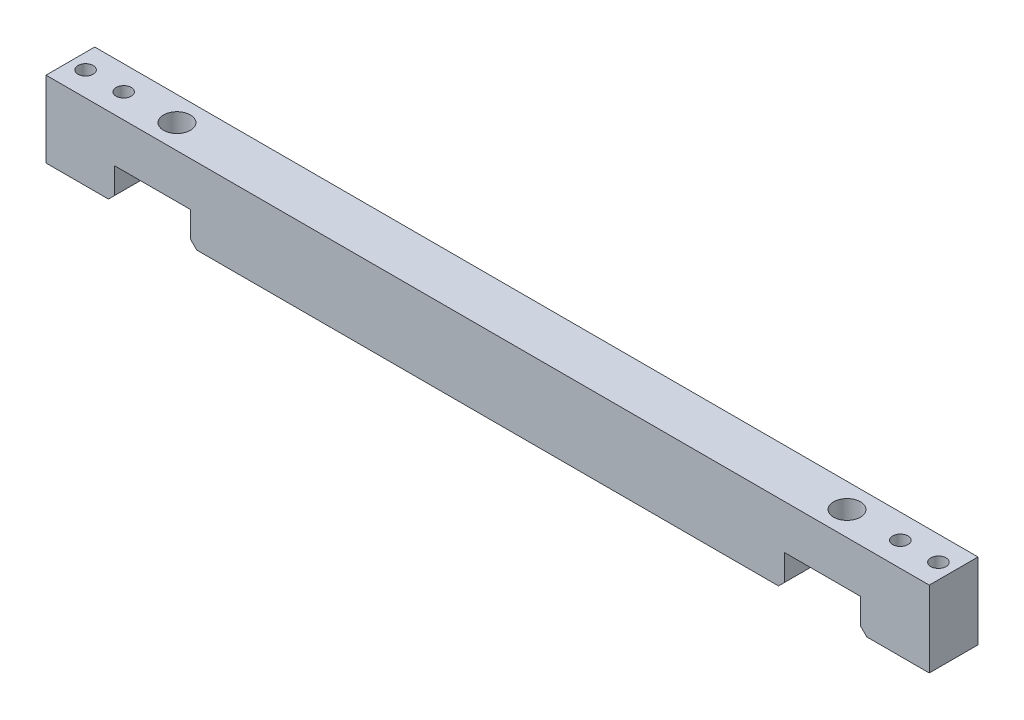
SolidWorks part; units mm, degrees
material "7075-T6 (SN)"
ref_plane "Front Plane" through (0, 0, 0) normal (0, 0, 1) x (1, 0, 0)
ref_plane "Top Plane" through (0, 0, 0) normal (0, 1, 0) x (1, 0, 0)
ref_plane "Right Plane" through (0, 0, 0) normal (1, 0, 0) x (0, 0, -1)
sketch "Sketch1" plane through (0, 0, 0) normal (0, 1, 0) x (1, 0, 0)
  line L1 (-145, 8) -> (145, 8)
  line L2 (-145, 8) -> (-145, -8)
  line L3 (-145, -8) -> (145, -8)
  line L4 (145, 8) -> (145, -8)
  line L5 (-145, 8) -> (145, -8) construction
  line L6 (-145, -8) -> (145, 8) construction
  point P0 (0, 0)
  dimension "D1" = 290
  dimension "D2" = 16
extrude "Boss-Extrude1" add sketch "Sketch1" along normal mid plane 25
hole_wizard "M5 Tapped Hole1" positions "Sketch4" profile "Sketch5" tap size "M5" standard "ISO" end condition through all
sketch "Sketch4" plane through (0, 12.5, 0) normal (0, 1, 0) x (1, 0, 0)
  point P0 (-110, 0)
  point P2 (110, 0)
  dimension "D1" = 110
  dimension "D2" = 110
sketch "Sketch5" plane through (-110, 12.5, 0) normal (1, 0, 0) x (0, 0, 1)
  line L0 (0, 0) -> (0, 25)
  line L1 (0, 25) -> (2.1, 25)
  line L2 (2.1, 25) -> (2.1, 0)
  line L5 (2.1, 0) -> (0, 0)
  line L11 (0, -6.35) -> (0, 107.95) construction
  dimension "Thru Tap Drill Dia." = 4.2
  dimension "Thru Tap Drill Depth" = 25
cosmetic thread "Hole Thread1"
cosmetic thread "Hole Thread2"
sketch "Sketch7" plane through (0, 0, 8) normal (0, 0, 1) x (1, 0, 0)
  line L0 (-145, -12.5) -> (145, -12.5) construction
  line L1 (97.5, -2) -> (122.5, -2)
  line L2 (97.5, -2) -> (97.5, -26.5478)
  line L3 (97.5, -26.5478) -> (122.5, -26.5478)
  line L4 (122.5, -2) -> (122.5, -26.5478)
  line L5 (112.1, 12.5) -> (107.9, 12.5) construction
  line L6 (112.1, 12.5) -> (107.9, 12.5) construction
  point P8 (110, 12.5)
  dimension "D1" = 10.5
  dimension "D2" = 25
  dimension "D3" = 12.5
extrude "Cut-Extrude2" cut sketch "Sketch7" against normal through all
chamfer "Chamfer1" distance 2 angle 45 2 edges at (122.5, -12.5, 0) (97.5, -12.5, 0)
mirror "Mirror1" about plane through (0, 0, 0) normal (1, 0, 0) of "Chamfer1", "Cut-Extrude2"
hole_wizard "G1/8 Tapped Hole1" positions "Sketch8" profile "Sketch9" tap size "G1/8" standard "ISO"
sketch "Sketch8" plane through (0, 12.5, 0) normal (0, 1, 0) x (1, 0, 0)
  point P0 (-110, 0)
  point P3 (110, 0)
sketch "Sketch9" plane through (-110, 12.5, 0) normal (1, 0, 0) x (0, 0, 1)
  line L0 (0, 0) -> (0, 11.6438)
  line L1 (0, 11.6438) -> (4.4, 9)
  line L2 (4.4, 9) -> (4.4, 0)
  line L5 (4.4, 0) -> (0, 0)
  line L10 (0, 11.6438) -> (-4.4, 9) construction
  line L11 (0, -6.35) -> (0, 107.95) construction
  dimension "Tap Drill Dia." = 8.8
  dimension "Tap Drill Depth" = 9
  dimension "Drill Angle" = 118
cosmetic thread "Hole Thread3"
cosmetic thread "Hole Thread4"
hole_wizard "M6 Tapped Hole1" positions "Sketch10" profile "Sketch11" tap size "M6" standard "ISO"
sketch "Sketch10" plane through (0, 12.5, 0) normal (0, 1, 0) x (1, 0, 0)
  line L0 (-145, 8) -> (-145, -8) construction
  line L1 (145, -8) -> (145, 8) construction
  point P0 (-140, 0)
  point P2 (-127.5, 0)
  point P4 (127.5, 0)
  point P6 (140, 0)
  dimension "D1" = 5
  dimension "D2" = 12.5
  dimension "D3" = 5
  dimension "D4" = 12.5
sketch "Sketch11" plane through (-140, 12.5, 0) normal (1, 0, 0) x (0, 0, 1)
  line L0 (0, 0) -> (0, 16.5022)
  line L1 (0, 16.5022) -> (2.5, 15)
  line L2 (2.5, 15) -> (2.5, 0)
  line L5 (2.5, 0) -> (0, 0)
  line L10 (0, 16.5022) -> (-2.5, 15) construction
  line L11 (0, -6.35) -> (0, 107.95) construction
  dimension "Tap Drill Dia." = 5
  dimension "Tap Drill Depth" = 15
  dimension "Drill Angle" = 118
cosmetic thread "Hole Thread5"
cosmetic thread "Hole Thread6"
cosmetic thread "Hole Thread7"
cosmetic thread "Hole Thread8"
